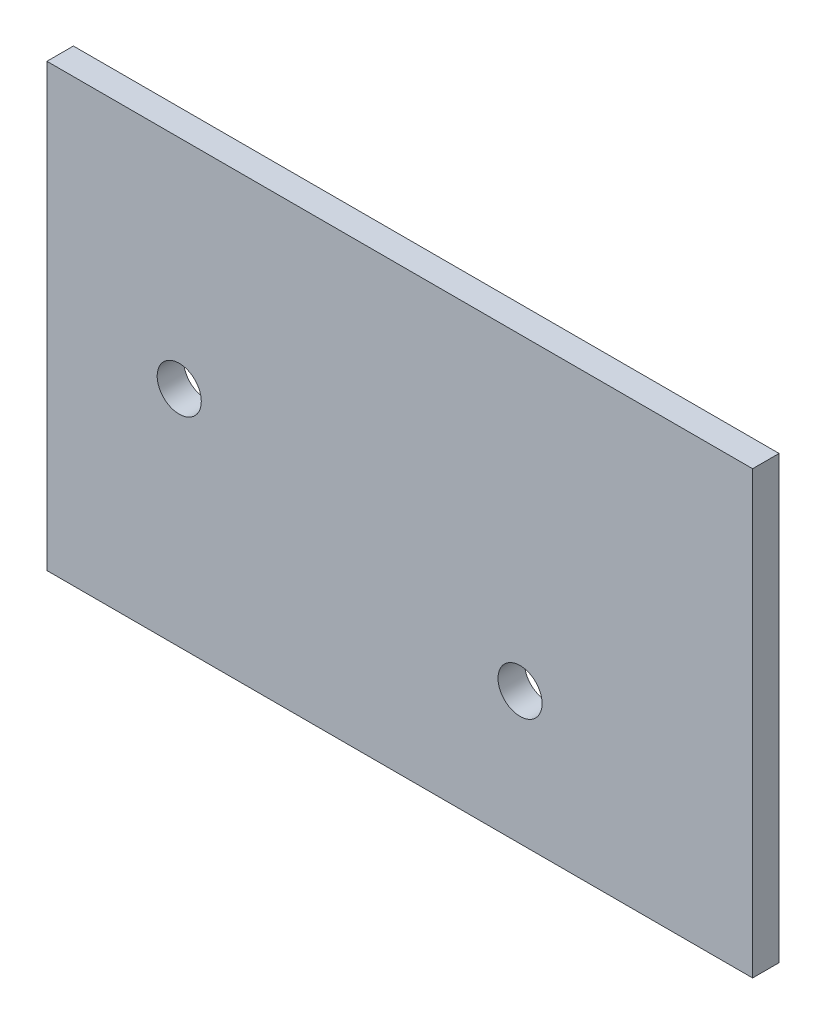
SolidWorks part; units mm, degrees
ref_plane "前基準面" through (0, 0, 0) normal (0, 0, 1) x (1, 0, 0)
ref_plane "上基準面" through (0, 0, 0) normal (0, 1, 0) x (1, 0, 0)
ref_plane "右基準面" through (0, 0, 0) normal (1, 0, 0) x (0, 0, -1)
sketch "草圖1" plane through (0, 0, 0) normal (0, 0, 1) x (1, 0, 0)
  line L1 (-15, 35) -> (65, 35)
  line L2 (-15, 35) -> (-15, -15)
  line L3 (-15, -15) -> (65, -15)
  line L4 (65, 35) -> (65, -15)
  dimension "D1" = 80
  dimension "D2" = 50
  dimension "D3" = 15
  dimension "D4" = 15
extrude "伸長1" add sketch "草圖1" along normal blind 3
sketch "草圖2" plane through (0, 0, 3) normal (0, 0, 1) x (1, 0, 0)
  line L0 (0, 10.3528) -> (38.637, 0) construction
  line L2 (38.637, 0) -> (0, 0) construction
  line L3 (0, 0) -> (0, 10.3528) construction
  circle A0 centre (0, 10.3528) radius 2.5
  circle A1 centre (38.637, 0) radius 2.5
  dimension "D3" = 5
  dimension "D2" = 40
  dimension "D1" = 15
extrude "伸長2" cut sketch "草圖2" against normal through all
